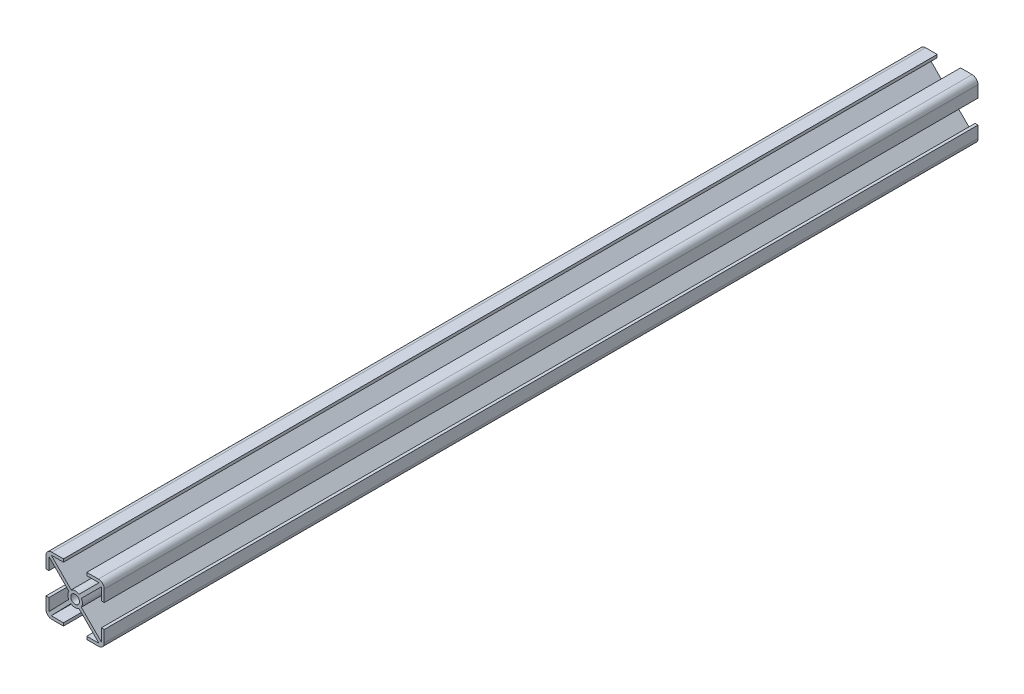
SolidWorks part; units mm, degrees
ref_plane "Plan de face" through (0, 0, 0) normal (0, 0, 1) x (1, 0, 0)
ref_plane "Plan de dessus" through (0, 0, 0) normal (0, 1, 0) x (1, 0, 0)
ref_plane "Plan de droite" through (0, 0, 0) normal (1, 0, 0) x (0, 0, -1)
sketch "Esquisse1" plane through (0, 0, 0) normal (0, 0, 1) x (1, 0, 0)
  line L0 (-19, 18.2) -> (-12.144, 11.2858)
  line L1 (0, 0) -> (-20, 0)
  line L2 (0, 0) -> (0, 20)
  line L3 (0, 20) -> (-20, 20)
  line L4 (-20, 0) -> (-20, 20)
  line L6 (-19, 18.2) -> (-19, 1.8)
  line L7 (-18.2, 1) -> (-1.8, 1)
  line L8 (-1, 18.2) -> (-1, 1.8)
  line L9 (-11.3575, 12.0994) -> (-18.2, 19)
  line L10 (-19, 1.8) -> (-12.2027, 8.8177)
  line L11 (-18.2, 1) -> (-11.4531, 7.9657)
  line L12 (-8.6781, 7.8781) -> (-1.8, 1)
  line L13 (-7.8781, 8.6781) -> (-1, 1.8)
  line L14 (-8.6781, 12.1219) -> (-1.8, 19)
  line L15 (-7.8781, 11.3219) -> (-1, 18.2)
  line L16 (-18.2, 19) -> (-1.8, 19)
  circle A0 centre (-10, 10) radius 1.5
  arc A1 (-8.6781, 12.1219) -> (-11.3575, 12.0994) centre (-10, 10) ccw
  arc A2 (-7.8781, 8.6781) -> (-7.8781, 11.3219) centre (-10, 10) ccw
  arc A3 (-11.4531, 7.9657) -> (-8.6781, 7.8781) centre (-10, 10) ccw
  arc A4 (-12.144, 11.2858) -> (-12.2027, 8.8177) centre (-10, 10) ccw
  dimension "D3" = 3
  dimension "D10" = 5
  dimension "D1" = 20
  dimension "D2" = 20
  dimension "D4" = 10
  dimension "D5" = 10
  dimension "D6" = 16.4
  dimension "D7" = 1
  dimension "D8" = 1
  dimension "D9" = 1
  dimension "D11" = 9
  dimension "D12" = 9.718
  dimension "D13" = 1.1316
  dimension "D14" = 9.7371
  dimension "D15" = 9.7699
  dimension "D16" = 1.1312
  dimension "D17" = 9.6975
  dimension "D18" = 9.7271
  dimension "D19" = 1.1314
  dimension "D20" = 9.7271
  dimension "D21" = 9.7271
  dimension "D22" = 1.1314
extrude "Boss.-Extru.1" add sketch "Esquisse1" along normal blind 300
fillet "Congé1" radius 2 4 edges at (0, 0, 150) (-20, 0, 150) (-20, 20, 150) (0, 20, 150)
sketch "Esquisse2" plane through (0, 0, 300) normal (0, 0, 1) x (1, 0, 0)
  line L0 (-2, 20) -> (-18, 20) construction
  line L1 (-14, 20) -> (-6, 20)
  line L2 (-14, 20) -> (-14, 19)
  line L3 (-14, 19) -> (-6, 19)
  line L4 (-6, 20) -> (-6, 19)
  line L5 (-20, 14) -> (-19, 14)
  line L6 (-20, 14) -> (-20, 6)
  line L7 (-20, 6) -> (-19, 6)
  line L8 (-19, 14) -> (-19, 6)
  line L9 (-14, 1) -> (-6, 1)
  line L10 (-14, 1) -> (-14, 0)
  line L11 (-14, 0) -> (-6, 0)
  line L12 (-6, 1) -> (-6, 0)
  line L13 (-1, 14) -> (0, 14)
  line L14 (-1, 14) -> (-1, 6)
  line L15 (-1, 6) -> (0, 6)
  line L16 (0, 14) -> (0, 6)
  line L17 (-18, 0) -> (-2, 0) construction
  line L18 (-20, 18) -> (-20, 2) construction
  line L19 (-19, 18.2) -> (-19, 1.8) construction
  line L20 (0, 2) -> (0, 18) construction
  line L21 (-1.8, 19) -> (-18.2, 19) construction
  line L22 (-1, 1.8) -> (-1, 18.2) construction
  line L23 (-18.2, 1) -> (-1.8, 1) construction
  dimension "D1" = 6
  dimension "D2" = 6
  dimension "D3" = 0
  dimension "D4" = 0
  dimension "D5" = 6
  dimension "D6" = 6
  dimension "D7" = 0
  dimension "D8" = 0
  dimension "D9" = 6
  dimension "D10" = 6
  dimension "D11" = 0
  dimension "D12" = 0
  dimension "D13" = 0
  dimension "D14" = 0
  dimension "D15" = 6
  dimension "D16" = 6
extrude "Enlèv. mat.-Extru.1" cut sketch "Esquisse2" against normal through all
